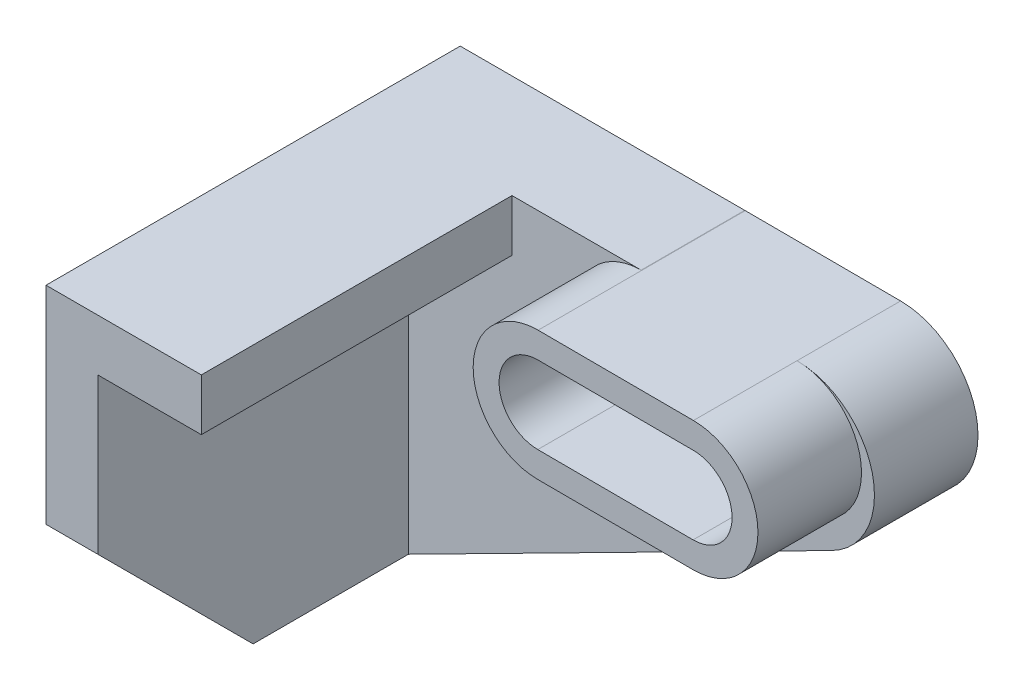
SolidWorks part; units mm, degrees
ref_plane "前基準面" through (0, 0, 0) normal (0, 0, 1) x (1, 0, 0)
ref_plane "上基準面" through (0, 0, 0) normal (0, 1, 0) x (1, 0, 0)
ref_plane "右基準面" through (0, 0, 0) normal (1, 0, 0) x (0, 0, -1)
sketch "草圖1" plane through (0, 0, 0) normal (0, 0, 1) x (1, 0, 0)
  line L0 (0, 0) -> (-29.9998, 0.1058) construction
  line L2 (0.0353, 9.9999) -> (0, 10.0001)
  line L3 (0.0353, 9.9999) -> (-29.9646, 10.1057) construction
  line L4 (0.0529, 14.9999) -> (-29.9469, 15.1057)
  line L5 (-29.9469, 15.1057) -> (-55, 15.1057)
  line L6 (-55, 15.1057) -> (-55, 5.1057)
  line L7 (-55, 5.1057) -> (-75, 5.1057)
  line L8 (-85, 15.1057) -> (-85, -54.8943)
  line L9 (-75, -54.8943) -> (6.7897, -13.3753)
  line L10 (-55, 15.1057) -> (-85, 15.1057)
  line L11 (-75, 5.1057) -> (-75, -54.8943)
  line L12 (-75, -54.8943) -> (-85, -54.8943)
  line L14 (0, 37.3676) -> (0, -42.4104) construction
  line L15 (-0.0529, -14.9999) -> (-30.0527, -14.8942) construction
  line L16 (-0.0353, -9.9999) -> (-30.0351, -9.8942) construction
  arc A1 (6.7897, -13.3753) -> (0.0529, 14.9999) centre (0, 0) ccw
  arc A2 (-29.9469, 15.1057) -> (-30.0527, 15.1057) centre (-29.9998, 0.1058) ccw
  arc A4 (-0.0353, -9.9999) -> (0.0353, 9.9999) centre (0, 0) ccw construction
  arc A5 (-29.9469, 15.1057) -> (-30.0527, -14.8942) centre (-29.9998, 0.1058) ccw construction
  arc A6 (-29.9646, 10.1057) -> (-30.0351, -9.8942) centre (-29.9998, 0.1058) ccw construction
  arc A8 (-0.0529, -14.9999) -> (0.0529, 14.9999) centre (0, 0) ccw construction
  point P2 (-14.9999, 0.0529)
  point P8 (0, 0)
  point P12 (0, 0)
  point P25 (0, 0)
  point P26 (0, 0)
  point P27 (0, 0)
  point P28 (-0.0353, -14.8942)
  point P29 (6.7897, -13.3753)
  dimension "D3" = 70
  dimension "D4" = 10
  dimension "D5" = 10
  dimension "D6" = 30
  dimension "D7" = 55
  dimension "D1" = 5
extrude "填料-伸長4" add sketch "草圖1" along normal blind 20
sketch "草圖3" plane through (0, 0, 0) normal (0, 0, 1) x (1, 0, 0)
  line L0 (-55, 15.1057) -> (-85, 15.1057)
  line L1 (-85, 15.1057) -> (-85, -54.8943)
  line L2 (-85, -54.8943) -> (-75, -54.8943)
  line L3 (-75, -54.8943) -> (-75, 5.1057)
  line L4 (-75, 5.1057) -> (-55, 5.1057)
  line L5 (-55, 15.1057) -> (-55, 5.1057) construction
  line L6 (-55, 5.1057) -> (-55, 15.1057)
  dimension "D1" = 30
  dimension "D2" = 10
  dimension "D3" = 10
  dimension "D4" = 55
extrude "填料-伸長5" add sketch "草圖3" along normal blind 80
sketch "草圖4" plane through (-75, 0, 0) normal (1, 0, 0) x (0, 0, -1)
  line L0 (-80, -24.8943) -> (-50, -54.8943)
  line L1 (-80, -54.8943) -> (-80, 5.1057) construction
  line L2 (-80, -54.8943) -> (-20, -54.8943) construction
  line L3 (-50, -54.8943) -> (-80, -54.8943)
  line L4 (-80, -54.8943) -> (-80, -24.8943)
  line L5 (-80, 15.1057) -> (-20, 15.1057) construction
  line L6 (0, -54.8943) -> (0, -13.3753) construction
  dimension "D1" = 40
  dimension "D2" = 50
extrude "除料-伸長2" cut sketch "草圖4" against normal blind 80
sketch "草圖5" plane through (0, 0, 0) normal (0, 0, 1) x (1, 0, 0)
  line L0 (0, 2.5) -> (-30, 2.6058) construction
  line L1 (-0.0264, -4.9999) -> (-30.0264, -4.8942)
  line L2 (0.0264, 10) -> (-29.9736, 10.1057)
  line L3 (-0.0441, -9.9999) -> (-30.0441, -9.8942)
  line L4 (0.0441, 14.9999) -> (-29.9559, 15.1057)
  line L5 (-55, 5.1057) -> (-55, 15.1057) construction
  line L6 (0.0529, 14.9999) -> (-29.9469, 15.1057) construction
  arc A0 (-0.0264, -4.9999) -> (0.0264, 10) centre (0, 2.5) ccw
  arc A1 (-29.9736, 10.1057) -> (-30.0264, -4.8942) centre (-30, 2.6058) ccw
  arc A2 (-29.9559, 15.1057) -> (-30.0441, -9.8942) centre (-30, 2.6058) ccw
  arc A3 (-0.0441, -9.9999) -> (0.0441, 14.9999) centre (0, 2.5) ccw
  point P2 (-15, 2.5529)
  dimension "D1" = 30
  dimension "D3" = 55
  dimension "D4" = 20
  dimension "D2" = 5
extrude "填料-伸長6" add sketch "草圖5" along normal blind 40
